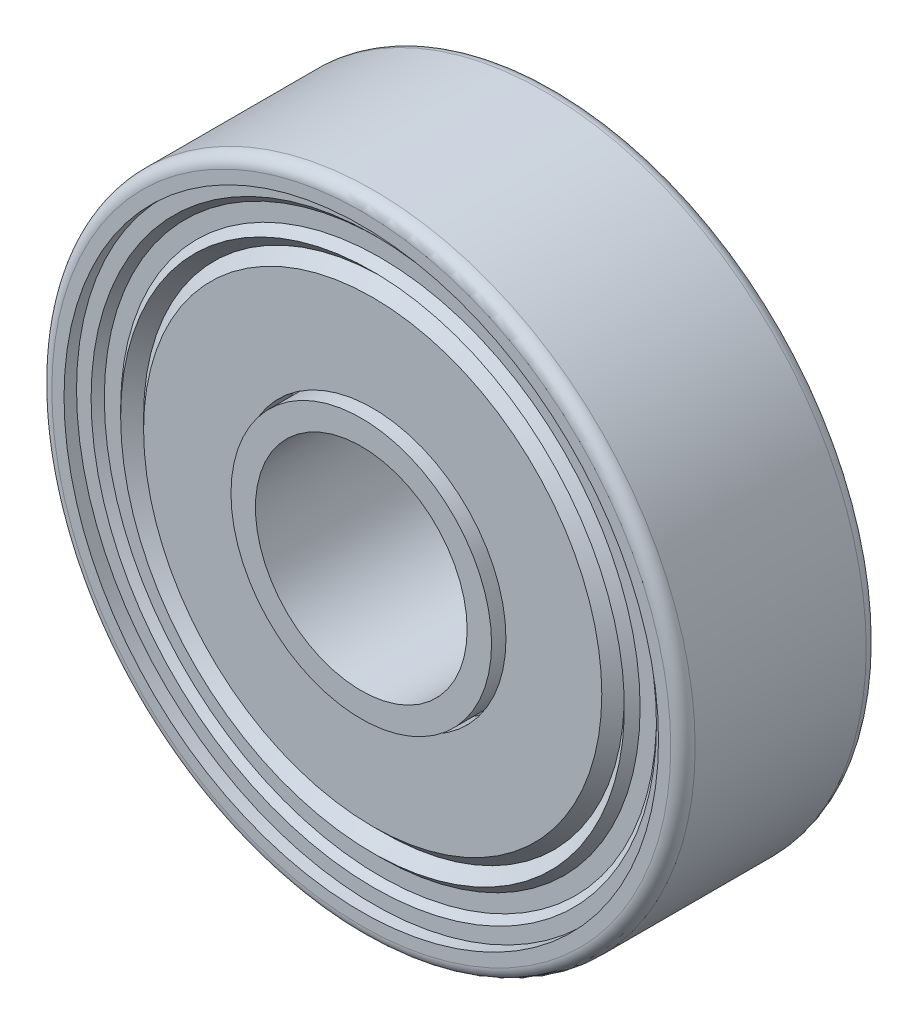
SolidWorks part; units mm, degrees
ref_plane "Front Plane" through (0, 0, 0) normal (0, 0, 1) x (1, 0, 0)
ref_plane "Top Plane" through (0, 0, 0) normal (0, 1, 0) x (1, 0, 0)
ref_plane "Right Plane" through (0, 0, 0) normal (1, 0, 0) x (0, 0, -1)
sketch "Sketch1" plane through (0, 0, 0) normal (0, 0, 1) x (1, 0, 0)
  circle A0 centre (0, 0) radius 7.9
  circle A1 centre (0, 0) radius 2.6
  dimension "D1" = 15.8
  dimension "D2" = 5.2
extrude "Boss-Extrude1" add sketch "Sketch1" along normal blind 4.8
sketch "Sketch2" plane through (0, 0, 0) normal (1, 0, 0) x (0, 0, -1)
  line L0 (-5.0238, 7.3) -> (-4.493, 7.3)
  line L1 (-4.493, 7.3) -> (-4.493, 6.9427)
  line L2 (-4.493, 6.9427) -> (-4.3306, 6.7803)
  line L3 (-4.3306, 6.7803) -> (-4.3306, 6.379)
  line L4 (-4.3306, 6.379) -> (-4.5241, 6.1855)
  line L5 (-4.5241, 6.1855) -> (-4.2424, 5.9038)
  line L6 (-4.2424, 5.9038) -> (-4.5196, 5.6265)
  line L7 (-4.5196, 5.6265) -> (-4.5196, 3.2729)
  line L8 (-4.5196, 3.2729) -> (-3.8174, 3.2729)
  line L9 (-3.8174, 3.2729) -> (-3.8174, 3.2)
  line L10 (-3.8174, 3.2) -> (-4.8797, 3.2)
  line L11 (-4.8797, 3.2) -> (-4.8797, 0)
  line L12 (2.64, 0) -> (-2.64, 0) construction
  line L13 (0, 7.9) -> (-4.8, 7.9) construction
  line L14 (-4.8797, 0) -> (-5.8692, 0)
  line L15 (-5.8692, 0) -> (-5.8692, 7.3)
  line L16 (-5.8692, 7.3) -> (-5.0238, 7.3)
  dimension "D1" = 3.2
  dimension "D2" = 0.6
revolve "Cut-Revolve1" cut sketch "Sketch2" angle 360 about L14
ref_plane "Plane1" through (0, 0, 2.4) normal (0, 0, 1) x (1, 0, 0)
mirror "Mirror1" about plane through (0, 0, 2.4) normal (0, 0, 1) of "Cut-Revolve1"
fillet "Fillet1" radius 0.3 2 edges at (7.9, 0, 4.8) (7.9, 0, 0)
